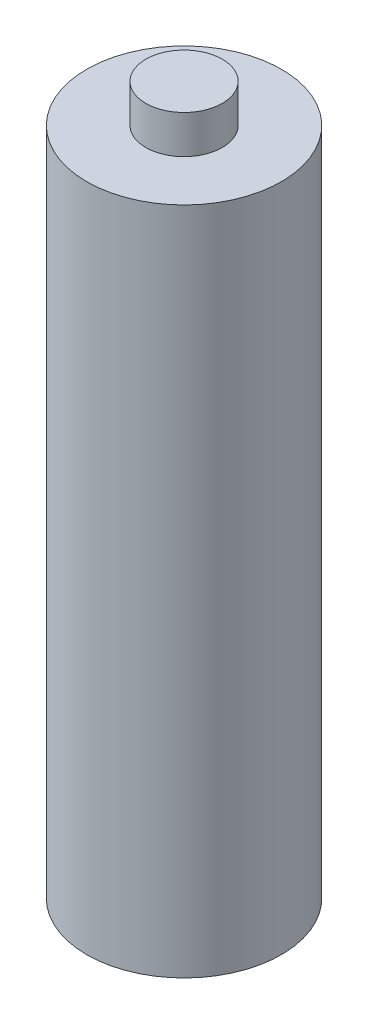
SolidWorks part; units mm, degrees
ref_plane "前视基准面" through (0, 0, 0) normal (0, 0, 1) x (1, 0, 0)
ref_plane "上视基准面" through (0, 0, 0) normal (0, 1, 0) x (1, 0, 0)
ref_plane "右视基准面" through (0, 0, 0) normal (1, 0, 0) x (0, 0, -1)
sketch "草图1" plane through (0, 0, 0) normal (0, 1, 0) x (1, 0, 0)
  circle A0 centre (0, 0) radius 10
extrude "凸台-拉伸1" add sketch "草图1" along normal blind 10
sketch "草图2" plane through (0, 10, 0) normal (0, 1, 0) x (1, 0, 0)
  circle A0 centre (0, 0) radius 25.46
extrude "凸台-拉伸2" add sketch "草图2" along normal blind 175
sketch "草图3" plane through (0, 185, 0) normal (0, 1, 0) x (1, 0, 0)
  circle A0 centre (0, 0) radius 10
extrude "凸台-拉伸3" add sketch "草图3" along normal blind 10
